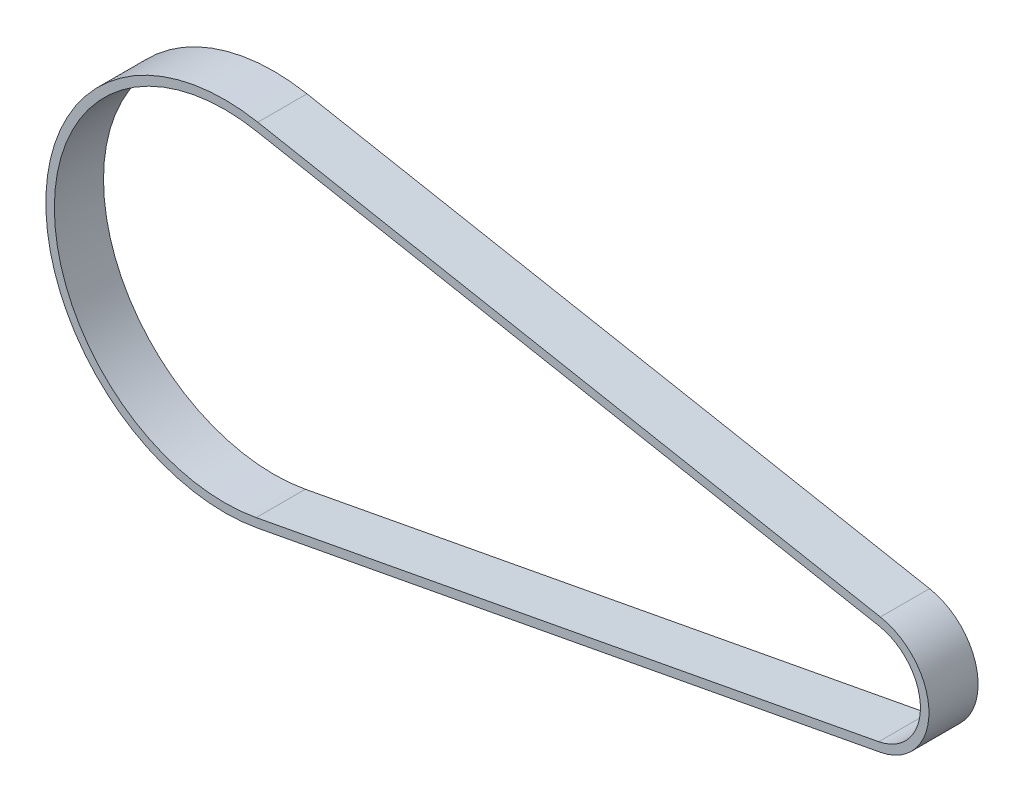
SolidWorks part; units mm, degrees
ref_plane "Front Plane" through (0, 0, 0) normal (0, 0, 1) x (1, 0, 0)
ref_plane "Top Plane" through (0, 0, 0) normal (0, 1, 0) x (1, 0, 0)
ref_plane "Right Plane" through (0, 0, 0) normal (1, 0, 0) x (0, 0, -1)
sketch "Sketch1" plane through (0, 0, 0) normal (0, 0, 1) x (1, 0, 0)
  line L0 (4.3082, 22.883) -> (85.3458, 7.626)
  line L1 (4.3082, -22.883) -> (85.3458, -7.626)
  arc A0 (4.3082, 22.883) -> (4.3082, -22.883) centre (0, 0) ccw
  arc A2 (85.3458, -7.626) -> (85.3458, 7.626) centre (83.91, 0) ccw
  dimension "D2" = 23.285
  dimension "D3" = 7.76
  dimension "D4" = 23.285
extrude "Boss-Extrude1" add sketch "Sketch1" along normal blind 6.4
sketch "Sketch2" plane through (0, 0, 6.4) normal (0, 0, 1) x (1, 0, 0)
  line L0 (4.1028, 21.7921) -> (85.1404, 6.5352)
  line L1 (4.1028, -21.7921) -> (85.1404, -6.5352)
  arc A0 (85.1404, -6.5352) -> (85.1404, 6.5352) centre (83.91, 0) ccw
  arc A1 (4.1028, 21.7921) -> (4.1028, -21.7921) centre (0, 0) ccw
  dimension "D1" = 44.35
  dimension "D2" = 13.3
extrude "Cut-Extrude1" cut sketch "Sketch2" against normal through all
